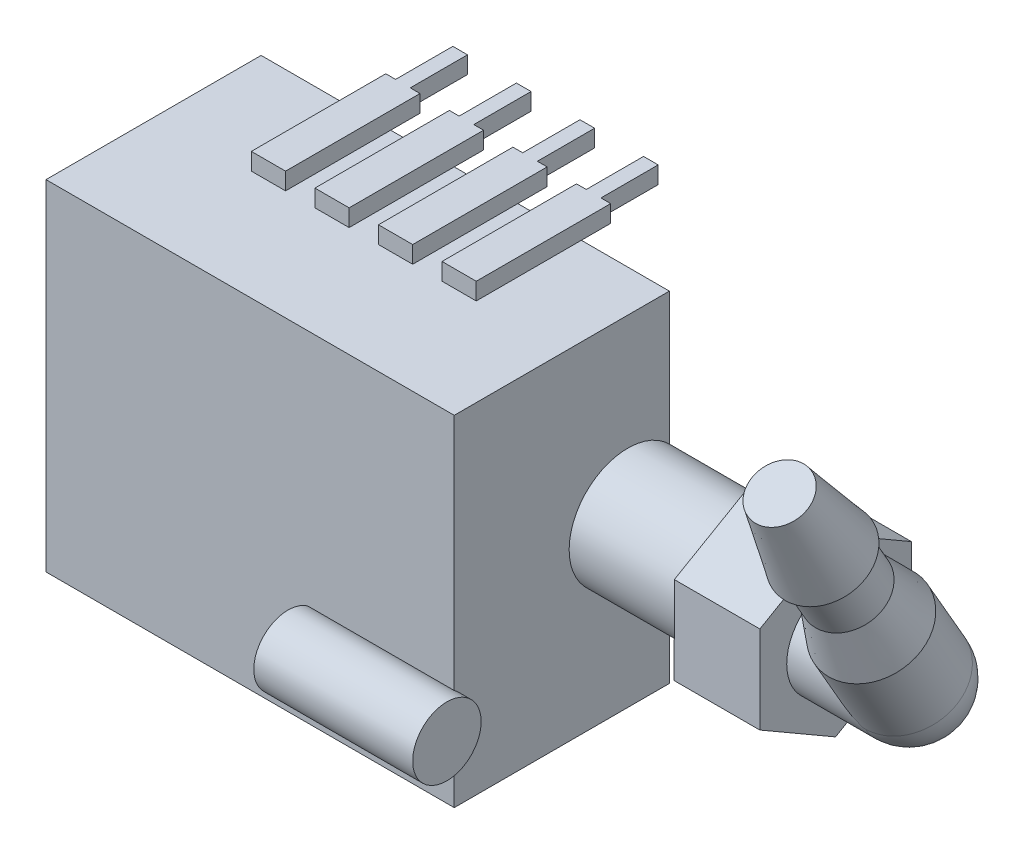
SolidWorks part; units mm, degrees
material "ABS"
ref_plane "Face" through (0, 0, 0) normal (0, 0, 1) x (1, 0, 0)
ref_plane "Dessus" through (0, 0, 0) normal (0, 1, 0) x (1, 0, 0)
ref_plane "Droite" through (0, 0, 0) normal (1, 0, 0) x (0, 0, -1)
sketch "Esquisse1" plane through (0, 0, 0) normal (0, 0, 1) x (1, 0, 0)
  line L0 (-7.9883, 7.1126) -> (-7.9883, -6.7874)
  line L1 (-7.9883, 7.1126) -> (8.7117, 7.1126)
  line L2 (-7.9883, -6.7874) -> (8.7117, -6.7874)
  line L3 (8.7117, 7.1126) -> (8.7117, -6.7874)
  dimension "D1" = 16.7
  dimension "D2" = 13.9
extrude "Extrusion1" add sketch "Esquisse1" against normal blind 8.8
sketch "Esquisse2" plane through (8.7117, 0, 0) normal (1, 0, 0) x (0, 0, -1)
  line L0 (0, -6.7874) -> (0, 7.1126) construction
  circle A0 centre (-0.8, -3.7874) radius 1.4
  dimension "D1" = 3
  dimension "D2" = 0.8
extrude "Extrusion2" add sketch "Esquisse2" against normal blind 6 and the other way blind 0.5
sketch "Esquisse3" plane through (8.7117, 0, 0) normal (1, 0, 0) x (0, 0, -1)
  line L0 (0, -2.6385) -> (0, 7.1126) construction
  circle A0 centre (7.1, 0) radius 2.4
  dimension "D1" = 7.1
  dimension "D2" = 4.8
extrude "Extrusion3" add sketch "Esquisse3" along normal blind 5
sketch "Esquisse4" plane through (13.7117, 0, 0) normal (1, 0, 0) x (0, 0, -1)
  line L0 (10.1981, -1.7931) -> (10.2019, 1.7865)
  line L1 (10.2019, 1.7865) -> (7.1038, 3.5796)
  line L2 (7.1038, 3.5796) -> (4.0019, 1.7931)
  line L3 (4.0019, 1.7931) -> (3.9981, -1.7865)
  line L4 (3.9981, -1.7865) -> (7.0962, -3.5796)
  line L5 (7.0962, -3.5796) -> (10.1981, -1.7931)
  circle A0 centre (7.1, 0) radius 3.1 construction
  dimension "D1" = 6.2
extrude "Extrusion4" add sketch "Esquisse4" along normal blind 3.5
sketch "Esquisse5" plane through (17.2117, 0, 0) normal (1, 0, 0) x (0, 0, -1)
  circle A0 centre (7.1, 0) radius 2
extrude "Extrusion5" add sketch "Esquisse5" along normal blind 5
fillet "Congé1" radius 2 1 edges at (22.2117, 0, -9.1)
sketch "Esquisse6" plane through (0, -0.3843, -0.2213) normal (0, 0.8666, 0.4991) x (-1, 0, 0)
  line L0 (-20.2117, -8.1525) -> (-20.2117, -4.1525) construction
  circle A0 centre (-20.2117, -6.1525) radius 2
extrude "Extrusion6" add sketch "Esquisse6" against normal blind 3 and the other way blind 2 draft 15
sketch "Esquisse7" plane through (0, 1.3488, 0.7768) normal (0, 0.8666, 0.4991) x (-1, 0, 0)
  circle A1 centre (-20.2117, -6.1525) radius 1.4641
  circle A2 centre (-20.2117, -6.1525) radius 1.4641
  dimension "D1" = 0
extrude "Extrusion7" add sketch "Esquisse7" along normal blind 2
sketch "Esquisse8" plane through (0, 3.0819, 1.775) normal (0, 0.8666, 0.4991) x (-1, 0, 0)
  circle A0 centre (-20.2117, -6.1525) radius 1.75
extrude "Extrusion8" add sketch "Esquisse8" along normal blind 3.5 draft 10
sketch "Esquisse9" plane through (0, -6.7874, 0) normal (0, -1, 0) x (1, 0, 0)
  line L0 (5.1117, -4.5) -> (5.1117, -10)
  line L1 (5.1117, -4.5) -> (3.7117, -4.5)
  line L2 (5.1117, -10) -> (4.7117, -10)
  line L3 (3.7117, -4.5) -> (3.7117, -10)
  line L4 (8.7117, -8.8) -> (8.7117, 0) construction
  line L5 (-7.9883, 0) -> (8.7117, 0) construction
  line L6 (-7.9883, -8.8) -> (8.7117, -8.8) construction
  line L7 (2.5117, -4.5) -> (2.5117, -10)
  line L8 (2.5117, -4.5) -> (1.1117, -4.5)
  line L9 (2.5117, -10) -> (2.1117, -10)
  line L10 (1.1117, -4.5) -> (1.1117, -10)
  line L11 (1.5117, -10) -> (1.5117, -12.3426)
  line L12 (1.5117, -12.3426) -> (2.1117, -12.3426)
  line L13 (2.1117, -10) -> (2.1117, -12.3426)
  line L14 (1.5117, -10) -> (1.1117, -10)
  line L15 (-0.0883, -4.5) -> (-0.0883, -10)
  line L16 (-0.0883, -4.5) -> (-1.4883, -4.5)
  line L17 (-0.0883, -10) -> (-0.4883, -10)
  line L18 (-1.4883, -4.5) -> (-1.4883, -10)
  line L19 (4.1117, -10) -> (4.1117, -12.3426)
  line L20 (-1.0883, -10) -> (-1.0883, -12.3426)
  line L21 (4.1117, -12.3426) -> (4.7117, -12.3426)
  line L22 (4.7117, -10) -> (4.7117, -12.3426)
  line L23 (4.1117, -10) -> (3.7117, -10)
  line L24 (-1.0883, -12.3426) -> (-0.4883, -12.3426)
  line L25 (-0.4883, -10) -> (-0.4883, -12.3426)
  line L26 (-1.0883, -10) -> (-1.4883, -10)
  line L27 (-2.6883, -4.5) -> (-2.6883, -10)
  line L28 (-2.6883, -4.5) -> (-4.0883, -4.5)
  line L29 (-2.6883, -10) -> (-3.0883, -10)
  line L30 (-4.0883, -4.5) -> (-4.0883, -10)
  line L31 (-3.6883, -10) -> (-3.6883, -12.3426)
  line L32 (-3.6883, -12.3426) -> (-3.0883, -12.3426)
  line L33 (-3.0883, -10) -> (-3.0883, -12.3426)
  line L34 (-3.6883, -10) -> (-4.0883, -10)
  dimension "D1" = 3.6
  dimension "D2" = 1.4
  dimension "D3" = 4.5
  dimension "D4" = 1.2
  dimension "D5" = 0.6
  dimension "D6" = 0.4
extrude "Extrusion9" add sketch "Esquisse9" along normal blind 0.7
sketch "Esquisse10" plane through (0, 7.1126, 0) normal (0, 1, 0) x (-1, 0, 0)
  line L8 (0.0883, -4.5) -> (0.0883, -10)
  line L9 (0.0883, -10) -> (0.4883, -10)
  line L10 (0.4883, -10) -> (0.4883, -12.3426)
  line L11 (0.4883, -12.3426) -> (1.0883, -12.3426)
  line L12 (1.0883, -12.3426) -> (1.0883, -10)
  line L13 (1.0883, -10) -> (1.4883, -10)
  line L14 (1.4883, -10) -> (1.4883, -4.5)
  line L15 (1.4883, -4.5) -> (0.0883, -4.5)
  line L16 (0.0883, -4.5) -> (0.0883, -10)
  line L17 (0.0883, -10) -> (0.4883, -10)
  line L18 (0.4883, -10) -> (0.4883, -12.3426)
  line L19 (0.4883, -12.3426) -> (1.0883, -12.3426)
  line L20 (1.0883, -12.3426) -> (1.0883, -10)
  line L21 (1.0883, -10) -> (1.4883, -10)
  line L22 (1.4883, -10) -> (1.4883, -4.5)
  line L23 (1.4883, -4.5) -> (0.0883, -4.5)
  line L24 (-2.5117, -10) -> (-2.1117, -10)
  line L25 (-2.5117, -4.5) -> (-2.5117, -10)
  line L26 (-1.1117, -4.5) -> (-2.5117, -4.5)
  line L27 (-1.1117, -10) -> (-1.1117, -4.5)
  line L28 (-1.5117, -10) -> (-1.1117, -10)
  line L29 (-1.5117, -12.3426) -> (-1.5117, -10)
  line L30 (-2.1117, -12.3426) -> (-1.5117, -12.3426)
  line L31 (-2.1117, -10) -> (-2.1117, -12.3426)
  line L32 (-2.5117, -10) -> (-2.1117, -10)
  line L33 (-2.5117, -4.5) -> (-2.5117, -10)
  line L34 (-1.1117, -4.5) -> (-2.5117, -4.5)
  line L35 (-1.1117, -10) -> (-1.1117, -4.5)
  line L36 (-1.5117, -10) -> (-1.1117, -10)
  line L37 (-1.5117, -12.3426) -> (-1.5117, -10)
  line L38 (-2.1117, -12.3426) -> (-1.5117, -12.3426)
  line L39 (-2.1117, -10) -> (-2.1117, -12.3426)
  line L40 (-4.7117, -10) -> (-4.7117, -12.3426)
  line L41 (-4.7117, -12.3426) -> (-4.1117, -12.3426)
  line L42 (-4.1117, -12.3426) -> (-4.1117, -10)
  line L43 (-4.1117, -10) -> (-3.7117, -10)
  line L44 (-3.7117, -10) -> (-3.7117, -4.5)
  line L45 (-3.7117, -4.5) -> (-5.1117, -4.5)
  line L46 (-5.1117, -4.5) -> (-5.1117, -10)
  line L47 (-5.1117, -10) -> (-4.7117, -10)
  line L48 (-4.7117, -10) -> (-4.7117, -12.3426)
  line L49 (-4.7117, -12.3426) -> (-4.1117, -12.3426)
  line L50 (-4.1117, -12.3426) -> (-4.1117, -10)
  line L51 (-4.1117, -10) -> (-3.7117, -10)
  line L52 (-3.7117, -10) -> (-3.7117, -4.5)
  line L53 (-3.7117, -4.5) -> (-5.1117, -4.5)
  line L54 (-5.1117, -4.5) -> (-5.1117, -10)
  line L55 (-5.1117, -10) -> (-4.7117, -10)
  line L56 (2.6883, -4.5) -> (2.6883, -10)
  line L57 (4.0883, -4.5) -> (2.6883, -4.5)
  line L58 (4.0883, -10) -> (4.0883, -4.5)
  line L59 (3.6883, -10) -> (4.0883, -10)
  line L60 (3.6883, -12.3426) -> (3.6883, -10)
  line L61 (3.0883, -12.3426) -> (3.6883, -12.3426)
  line L62 (3.0883, -10) -> (3.0883, -12.3426)
  line L63 (2.6883, -10) -> (3.0883, -10)
  line L64 (2.6883, -4.5) -> (2.6883, -10)
  line L65 (4.0883, -4.5) -> (2.6883, -4.5)
  line L66 (4.0883, -10) -> (4.0883, -4.5)
  line L67 (3.6883, -10) -> (4.0883, -10)
  line L68 (3.6883, -12.3426) -> (3.6883, -10)
  line L69 (3.0883, -12.3426) -> (3.6883, -12.3426)
  line L70 (3.0883, -10) -> (3.0883, -12.3426)
  line L71 (2.6883, -10) -> (3.0883, -10)
  dimension "D1" = 0
  dimension "D2" = 0
  dimension "D3" = 0
  dimension "D4" = 0
extrude "Extrusion10" add sketch "Esquisse10" along normal blind 0.7
